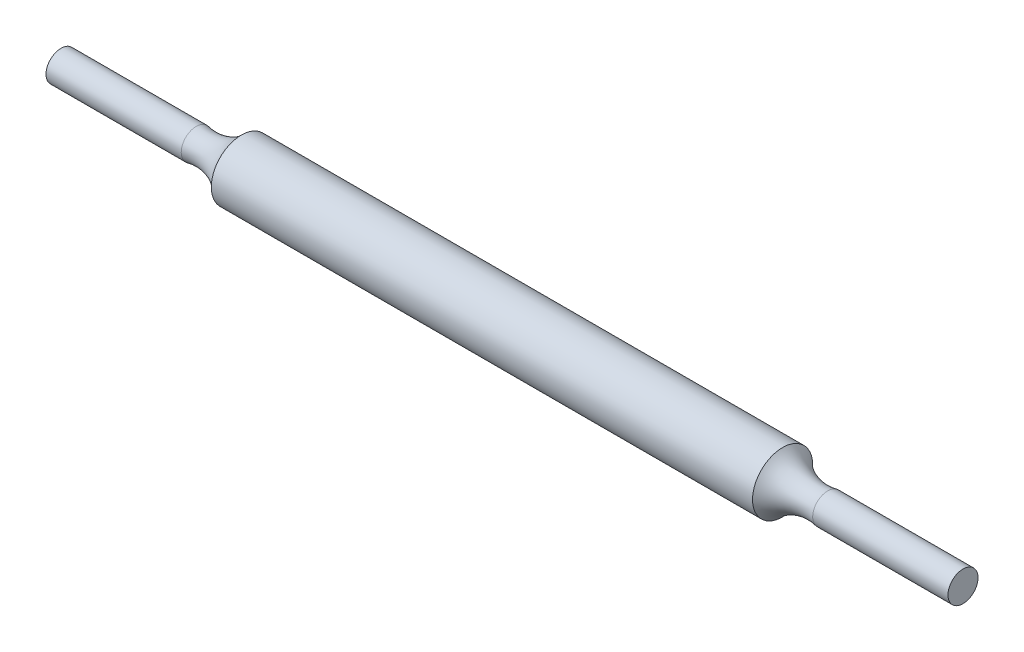
SolidWorks part; units mm, degrees
ref_plane "Front Plane" through (0, 0, 0) normal (0, 0, 1) x (1, 0, 0)
ref_plane "Top Plane" through (0, 0, 0) normal (0, 1, 0) x (1, 0, 0)
ref_plane "Right Plane" through (0, 0, 0) normal (1, 0, 0) x (0, 0, -1)
sketch "Sketch1" plane through (0, 0, 0) normal (0, 1, 0) x (1, 0, 0)
  line L0 (-29.9976, 0) -> (30.0024, 0)
  line L1 (30.0024, 0) -> (30.0024, 1)
  line L2 (-18.0024, 2) -> (18.0024, 2)
  line L3 (30.0024, 1) -> (21.0024, 1)
  line L4 (0, 2) -> (0, 0) construction
  line L5 (-29.9976, 1) -> (-21.0024, 1)
  line L6 (-29.9976, 0) -> (-29.9976, 1)
  arc A4 (-21.0024, 1) -> (-18.0024, 2) centre (-20.3466, 4.0327) ccw
  arc A5 (21.0024, 1) -> (18.0024, 2) centre (20.3466, 4.0327) cw
  point P13 (30.0024, 0)
  point P14 (0, 0)
  point P15 (0, 0)
  point P16 (0, 0)
  dimension "D1" = 2
  dimension "D2" = 1
  dimension "D3" = 3
  dimension "D4" = 9
  dimension "D5" = 60
revolve "Revolve1" add sketch "Sketch1" angle 360 about L0
